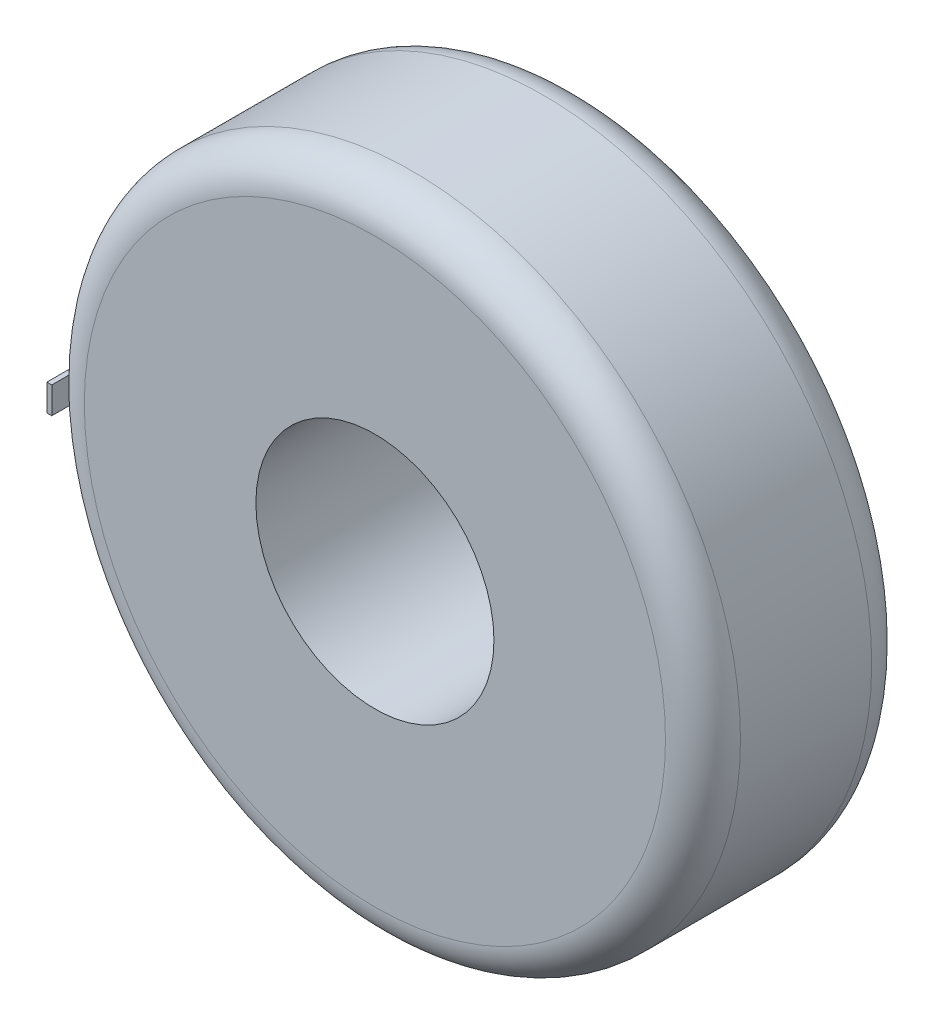
SolidWorks part; units mm, degrees
ref_plane "Alzado" through (0, 0, 0) normal (0, 0, 1) x (1, 0, 0)
ref_plane "Planta" through (0, 0, 0) normal (0, 1, 0) x (1, 0, 0)
ref_plane "Vista lateral" through (0, 0, 0) normal (1, 0, 0) x (0, 0, -1)
sketch "Croquis1" plane through (0, 0, 0) normal (0, 0, 1) x (1, 0, 0)
  circle A0 centre (0, 0) radius 17.5
  circle A1 centre (0, 0) radius 6.35
  dimension "D1" = 35
  dimension "D2" = 12.7
extrude "Saliente-Extruir1" add sketch "Croquis1" along normal blind 11
fillet "Redondeo1" radius 2 2 edges at (17.5, 0, 0) (17.5, 0, 11)
sketch "Croquis2" plane through (0, 0, 11) normal (0, 0, 1) x (1, 0, 0)
  line L1 (-17.5, 0) -> (-17.2369, 0)
  line L2 (-17.5, 0) -> (-17.5, -1.425)
  line L3 (-17.5, -1.425) -> (-17.2369, -1.425)
  line L4 (-17.2369, 0) -> (-17.2369, -1.425)
  circle A0 centre (0, 0) radius 17.5 construction
extrude "Saliente-Extruir2" add sketch "Croquis2" against normal up to surface (11 mm away) up to face at (15.5, 0, 0)
